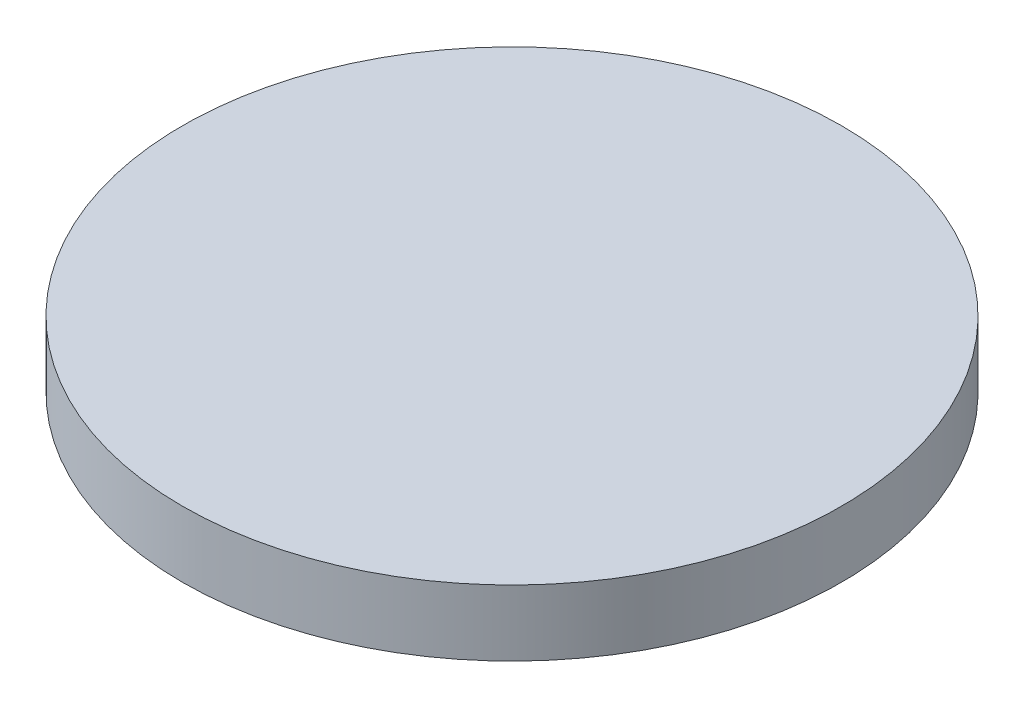
SolidWorks part; units mm, degrees
ref_plane "Front Plane" through (0, 0, 0) normal (0, 0, 1) x (1, 0, 0)
ref_plane "Top Plane" through (0, 0, 0) normal (0, 1, 0) x (1, 0, 0)
ref_plane "Right Plane" through (0, 0, 0) normal (1, 0, 0) x (0, 0, -1)
sketch "Sketch1" plane through (0, 0, 0) normal (0, 1, 0) x (1, 0, 0)
  circle A0 centre (0, 0) radius 8
  dimension "D1" = 16
extrude "Boss-Extrude1" add sketch "Sketch1" along normal blind 1.6
